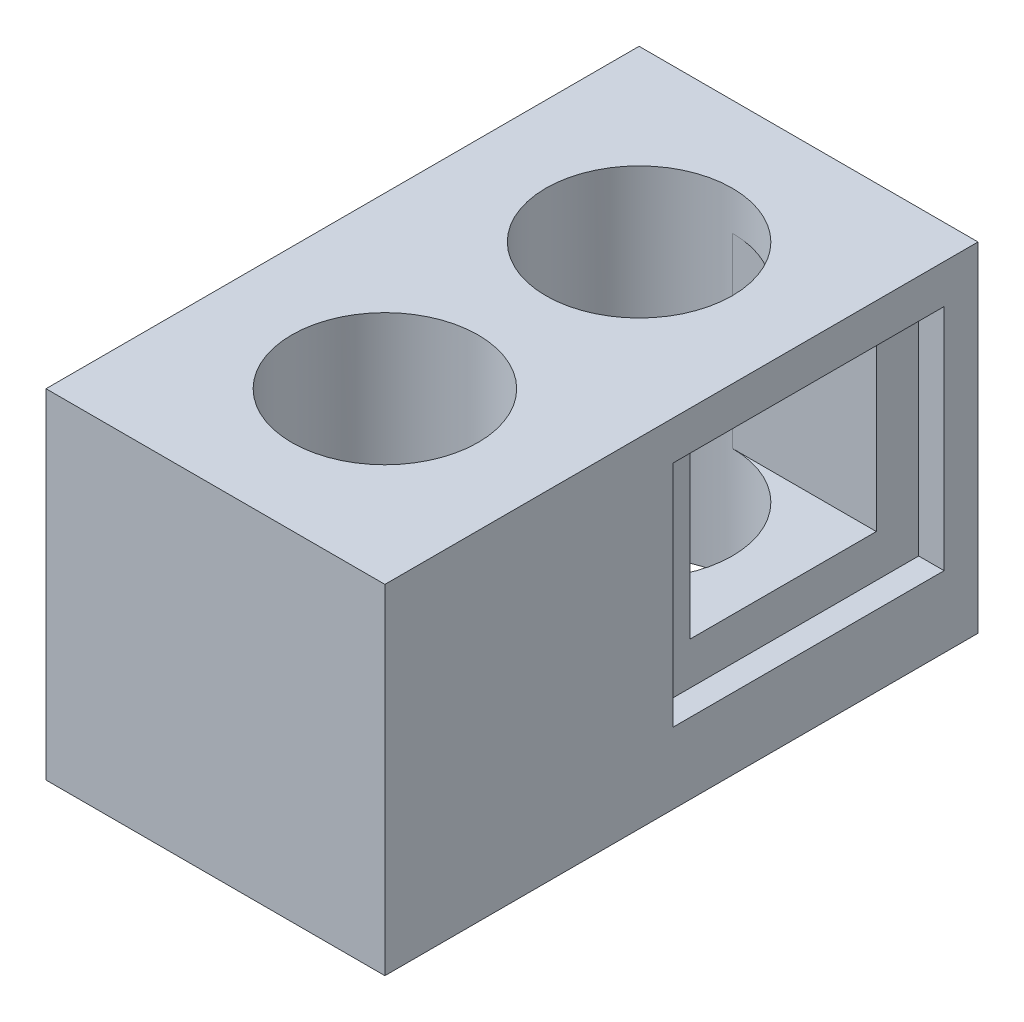
SolidWorks part; units mm, degrees
ref_plane "Alzado" through (0, 0, 0) normal (0, 0, 1) x (1, 0, 0)
ref_plane "Planta" through (0, 0, 0) normal (0, 1, 0) x (1, 0, 0)
ref_plane "Vista lateral" through (0, 0, 0) normal (1, 0, 0) x (0, 0, -1)
sketch "Croquis1" plane through (0, 0, 0) normal (0, 1, 0) x (1, 0, 0)
  line L0 (63.781, -89.5414) -> (63.781, -64.5068) construction
  line L1 (73.781, -64.5414) -> (53.781, -64.5414)
  line L2 (73.781, -64.5414) -> (73.781, -99.5414)
  line L3 (73.781, -99.5414) -> (53.781, -99.5414)
  line L4 (53.781, -64.5414) -> (53.781, -99.5414)
  line L5 (73.781, -64.5414) -> (53.781, -99.5414) construction
  line L6 (73.781, -99.5414) -> (53.781, -64.5414) construction
  circle A1 centre (63.781, -89.5414) radius 5
  circle A2 centre (63.781, -74.5414) radius 5
  dimension "D3" = 10
  dimension "D5" = 15
  dimension "D1" = 20
  dimension "D2" = 10
  dimension "D4" = 10
extrude "Saliente-Extruir1" add sketch "Croquis1" along normal blind 20
sketch "Croquis2" plane through (73.781, 0, 0) normal (1, 0, 0) x (0, 0, -1)
  line L1 (-64.5414, 0) -> (-88, 0) construction
  line L2 (-64.5414, 0) -> (-64.5414, 20) construction
  line L3 (-64.5414, 20) -> (-99.5414, 20) construction
  circle A0 centre (-74.5414, 12.2) radius 2
  point P0 (-74.5414, 12.2)
  dimension "D1" = 10
  dimension "D2" = 12.2
extrude "Saliente-Extruir2" add sketch "Croquis2" along normal blind 8
sketch "Croquis3" plane through (0, 20, 0) normal (0, 1, 0) x (1, 0, 0)
  circle A0 centre (63.781, -89.5414) radius 5 construction
  circle A1 centre (63.781, -74.5414) radius 5 construction
  circle A2 centre (63.781, -89.5414) radius 5 construction
  circle A3 centre (63.781, -74.5414) radius 5 construction
  circle A4 centre (63.781, -74.5414) radius 5.5
  circle A5 centre (63.781, -89.5414) radius 5.5
  dimension "D1" = 11
  dimension "D2" = 11
extrude "Cortar-Extruir1" cut sketch "Croquis3" against normal through all and the other way through all
sketch "Croquis4" plane through (81.781, 0, 0) normal (1, 0, 0) x (0, 0, -1)
  line L1 (-69.0414, 17.7) -> (-80.0414, 17.7)
  line L2 (-69.0414, 17.7) -> (-69.0414, 6.7)
  line L3 (-69.0414, 6.7) -> (-80.0414, 6.7)
  line L4 (-80.0414, 17.7) -> (-80.0414, 6.7)
  line L5 (-69.0414, 17.7) -> (-80.0414, 6.7) construction
  line L6 (-69.0414, 6.7) -> (-80.0414, 17.7) construction
  point P0 (-74.5414, 12.2)
  dimension "D1" = 11
  dimension "D2" = 11
extrude "Cortar-Extruir2" cut sketch "Croquis4" against normal blind 18
sketch "Croquis7" plane through (73.781, 0, 0) normal (1, 0, 0) x (0, 0, -1)
  line L0 (-80.0414, 17.7) -> (-69.0414, 17.7) construction
  line L1 (-82.5414, 17.7) -> (-66.5414, 17.7)
  line L2 (-82.5414, 17.7) -> (-82.5414, 4.2)
  line L3 (-82.5414, 4.2) -> (-66.5414, 4.2)
  line L4 (-66.5414, 17.7) -> (-66.5414, 4.2)
  line L5 (-69.0414, 17.7) -> (-69.0414, 6.7) construction
  line L6 (-80.0414, 6.7) -> (-80.0414, 17.7) construction
  line L7 (-69.0414, 6.7) -> (-80.0414, 6.7) construction
  dimension "D1" = 0
  dimension "D2" = 2.5
  dimension "D3" = 2.5
  dimension "D4" = 2.5
extrude "Cortar-Extruir3" cut sketch "Croquis7" against normal blind 1.5
